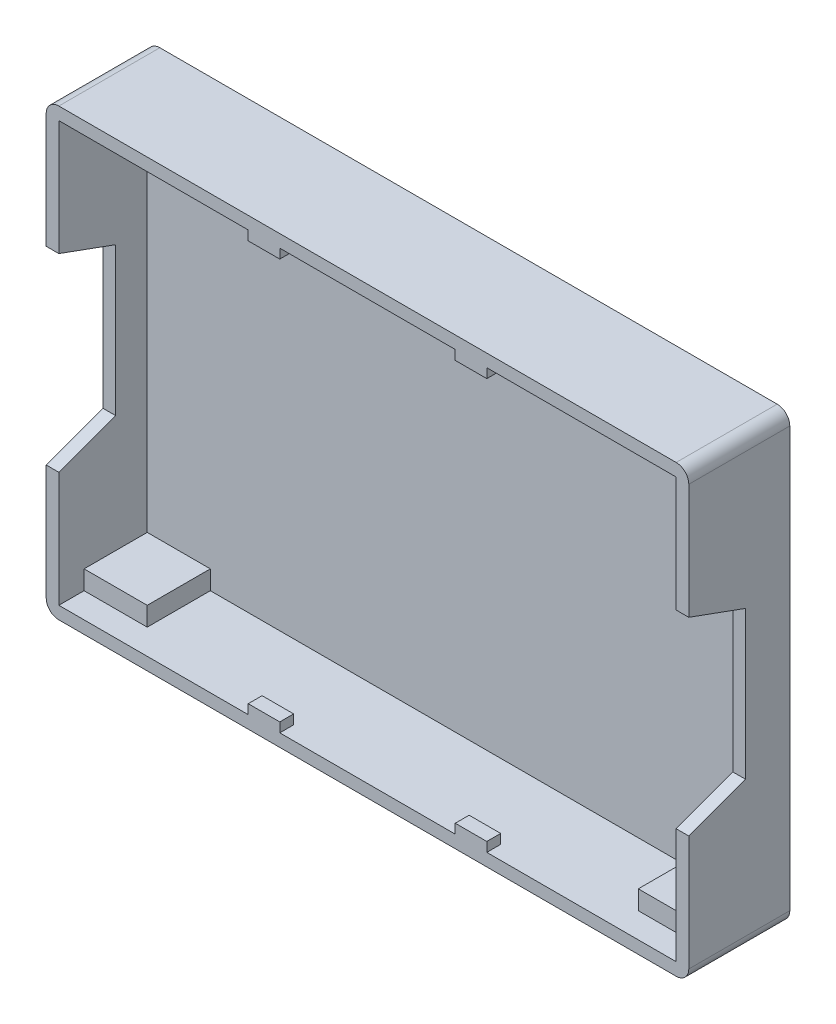
SolidWorks part; units mm, degrees
ref_plane "Front Plane" through (0, 0, 0) normal (1, 0, 0) x (0, 1, 0)
ref_plane "Top Plane" through (0, 0, 0) normal (0, 0, 1) x (0, 1, 0)
ref_plane "Right Plane" through (0, 0, 0) normal (0, 1, 0) x (-1, 0, 0)
sketch "Sketch1" plane through (0, 0, 0) normal (0, 0, 1) x (0, 1, 0)
  line L0 (-35.25, -50.9) -> (-35.25, 50.9)
  line L1 (-33.25, -48.9) -> (33.25, -48.9)
  line L2 (-33.25, -48.9) -> (-33.25, 48.9)
  line L3 (-33.25, 48.9) -> (33.25, 48.9)
  line L4 (33.25, -48.9) -> (33.25, 48.9)
  line L5 (-33.25, -48.9) -> (33.25, 48.9) construction
  line L6 (-33.25, 48.9) -> (33.25, -48.9) construction
  line L7 (-35.25, 50.9) -> (35.25, 50.9)
  line L8 (35.25, -50.9) -> (35.25, 50.9)
  line L9 (-35.25, -50.9) -> (35.25, -50.9)
  point P0 (0, 0)
  dimension "D1" = 66.5
  dimension "D2" = 97.8
  dimension "D3" = 2
extrude "Boss-Extrude1-board-4mm" add sketch "Sketch1" along normal blind 4
sketch "Sketch2" plane through (0, 0, 0) normal (0, 0, -1) x (1, 0, 0)
  line L0 (48.9, -33.25) -> (-48.9, -33.25) construction
  line L1 (-48.9, 33.25) -> (48.9, 33.25) construction
  line L2 (48.9, -33.25) -> (-48.9, -33.25) construction
  line L3 (-48.9, 33.25) -> (48.9, 33.25) construction
  line L4 (50.9, -35.25) -> (50.9, 35.25)
  line L5 (50.9, 35.25) -> (-50.9, 35.25)
  line L6 (-50.9, 35.25) -> (-50.9, -35.25)
  line L7 (-50.9, -35.25) -> (50.9, -35.25)
  line L8 (50.9, -35.25) -> (50.9, 35.25)
  line L9 (50.9, 35.25) -> (-50.9, 35.25)
  line L10 (-50.9, 35.25) -> (-50.9, -35.25)
  line L11 (-50.9, -35.25) -> (50.9, -35.25)
  line L12 (-48.9, 30.25) -> (-38.9, 30.25)
  line L13 (48.9, -30.25) -> (38.9, -30.25)
  line L14 (-48.9, 30.25) -> (-48.9, -30.25)
  line L15 (48.9, 30.25) -> (48.9, -30.25)
  line L16 (-38.9, 30.25) -> (-38.9, 33.25)
  line L17 (-38.9, 33.25) -> (38.9, 33.25)
  line L18 (38.9, 33.25) -> (38.9, 30.25)
  line L19 (-70.7302, 0) -> (65.1142, 0) construction
  line L20 (-48.9, -33.25) -> (-48.9, 33.25) construction
  line L21 (48.9, 33.25) -> (48.9, -33.25) construction
  line L22 (38.9, 30.25) -> (48.9, 30.25)
  line L23 (-48.9, 30.25) -> (48.9, 30.25) construction
  line L24 (38.9, -33.25) -> (38.9, -30.25)
  line L25 (-38.9, -33.25) -> (38.9, -33.25)
  line L26 (-38.9, -30.25) -> (-38.9, -33.25)
  line L27 (-38.9, -30.25) -> (-48.9, -30.25)
  line L28 (48.9, -30.25) -> (-48.9, -30.25) construction
  dimension "D4" = 10
  dimension "D5" = 10
  dimension "D1" = 0
  dimension "D2" = 3
extrude "Boss-Extrude2-under-10ms" add sketch "Sketch2" along normal blind 10
sketch "Sketch3" plane through (0, 0, -10) normal (0, 0, -1) x (1, 0, 0)
  line L1 (-50.9, 35.25) -> (50.9, 35.25)
  line L2 (-50.9, 35.25) -> (-50.9, -35.25)
  line L3 (-50.9, -35.25) -> (50.9, -35.25)
  line L4 (50.9, 35.25) -> (50.9, -35.25)
extrude "Boss-Extrude3-bottom-cover-2mm" add sketch "Sketch3" along normal blind 2
ref_plane "Plane1-pcb-up-surface" through (0, 0, 1.8) normal (0, 0, 1) x (1, 0, 0)
sketch "Sketch4" plane through (0, 0, 1.8) normal (0, 0, 1) x (1, 0, 0)
  line L0 (50.9, 35.25) -> (-50.9, 35.25) construction
  line L1 (-18.9, 35.25) -> (-13.9, 35.25)
  line L2 (-18.9, 35.25) -> (-18.9, 31.75)
  line L3 (-18.9, -35.25) -> (-13.9, -35.25)
  line L4 (-13.9, 35.25) -> (-13.9, 31.75)
  line L5 (-50.9, -35.25) -> (50.9, -35.25) construction
  line L6 (0, 0) -> (0, 44.7823) construction
  line L7 (-18.9, 31.75) -> (-13.9, 31.75)
  line L8 (-18.9, -31.75) -> (-13.9, -31.75)
  line L9 (48.9, 33.25) -> (-48.9, 33.25) construction
  line L10 (-38.9, 30.25) -> (-38.9, 33.25) construction
  line L11 (-18.9, -31.75) -> (-18.9, -35.25)
  line L12 (-13.9, -31.75) -> (-13.9, -35.25)
  line L13 (13.9, -31.75) -> (13.9, -35.25)
  line L14 (18.9, -31.75) -> (18.9, -35.25)
  line L15 (18.9, -31.75) -> (13.9, -31.75)
  line L16 (18.9, -35.25) -> (13.9, -35.25)
  line L17 (18.9, 31.75) -> (13.9, 31.75)
  line L18 (13.9, 35.25) -> (13.9, 31.75)
  line L19 (18.9, 35.25) -> (18.9, 31.75)
  line L20 (18.9, 35.25) -> (13.9, 35.25)
  dimension "D1" = 3.5
  dimension "D2" = 1.5
  dimension "D3" = 20
  dimension "D4" = 5
extrude "Boss-Extrude4" add sketch "Sketch4" along normal up to surface (2.2 mm away) up to face at (0, 0, 4)
sketch "Sketch5" plane through (0, 0, 4) normal (0, 0, 1) x (1, 0, 0)
  line L1 (-64.1932, -15) -> (64.1932, -15)
  line L2 (-64.1932, -15) -> (-64.1932, 15)
  line L3 (-64.1932, 15) -> (64.1932, 15)
  line L4 (64.1932, -15) -> (64.1932, 15)
  line L5 (-64.1932, -15) -> (64.1932, 15) construction
  line L6 (-64.1932, 15) -> (64.1932, -15) construction
  point P0 (0, 0)
  dimension "D1" = 30
extrude "Cut-Extrude1-cut-usb" cut sketch "Sketch5" against normal offset from surface 5 draft 20
fillet "Fillet1" radius 2 4 edges at (-50.9, -35.25, -4) (-50.9, 35.25, -4) (50.9, 35.25, -4) (50.9, -35.25, -4)
